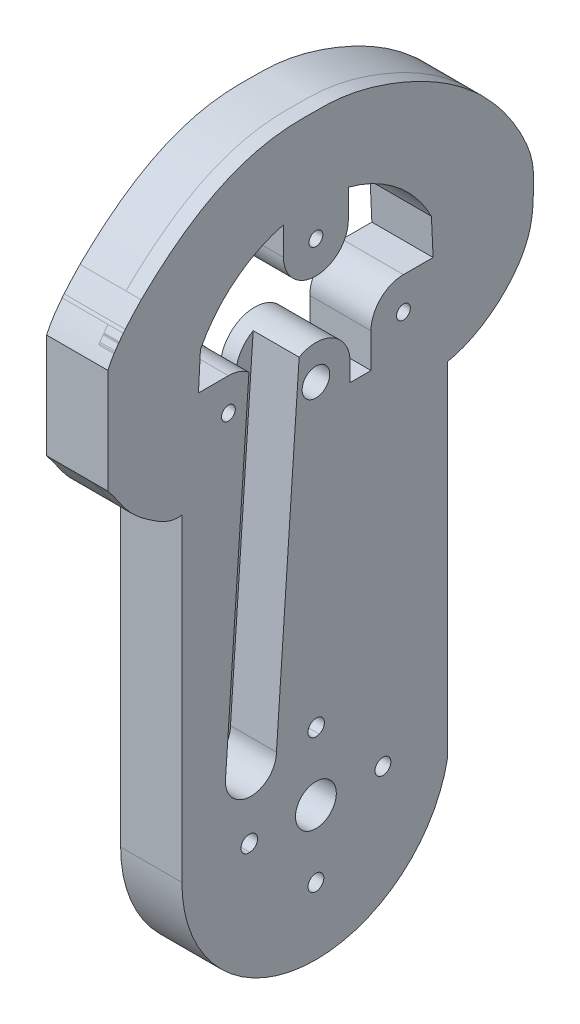
SolidWorks part; units mm, degrees
ref_plane "Plan de face" through (0, 0, 0) normal (0, 0, 1) x (1, 0, 0)
ref_plane "Plan de dessus" through (0, 0, 0) normal (0, 1, 0) x (1, 0, 0)
ref_plane "Plan de droite" through (0, 0, 0) normal (1, 0, 0) x (0, 0, -1)
sketch "Esquisse1" plane through (0, 0, 0) normal (1, 0, 0) x (0, 0, -1)
  line L19 (-6.1849, 6.1035) -> (-6.1849, 11.6469)
  line L20 (6.5151, 6.1035) -> (6.5151, 11.6469)
  line L21 (-10.6299, -14.9225) -> (-10.6299, -21.6694)
  line L22 (-16.9799, -8.5725) -> (-22.849, -8.5725)
  line L23 (17.3101, -8.5725) -> (23.1259, -8.5725)
  line L24 (-40.6082, -16.1449) -> (-40.6083, -16.3483)
  line L25 (0.1651, -90) -> (0.1651, -116.2575) construction
  line L26 (10.9601, -14.9225) -> (10.9601, -21.6694)
  line L27 (0.1651, 0) -> (0.1651, -90) construction
  line L28 (-26.0924, -27.6543) -> (-26.0924, -90) construction
  line L29 (10.9601, -21.6694) -> (6.8802, -21.6694)
  line L30 (6.8802, -21.6694) -> (6.8802, -18.2245)
  line L31 (-6.55, -18.2245) -> (-6.55, -21.6694)
  line L32 (-6.55, -21.6694) -> (-10.6299, -21.6694)
  line L33 (-26.0924, -90) -> (25.954, -90) construction
  line L34 (25.954, -90) -> (25.954, -27.6542) construction
  line L35 (-40.6082, 4.1425) -> (-40.6082, -12.7)
  line L36 (-26.0924, -27.6543) -> (-26.0924, -90)
  line L37 (25.954, -27.6542) -> (25.954, -90)
  line L38 (-40.6082, -16.1449) -> (-40.6082, -12.7)
  line L39 (-37.9035, 8.4934) -> (-36.4387, 10.3053) construction
  line L40 (-22.4631, -1.4086) -> (-22.849, -8.5725)
  line L41 (22.7933, -1.4086) -> (23.1259, -8.5725)
  circle A4 centre (-16.9799, -14.9225) radius 1.3525
  arc A5 (22.7933, -1.4086) -> (6.5151, 11.6469) centre (0.1651, -12.9465) ccw
  arc A6 (6.8802, -18.2245) -> (-6.55, -18.2245) centre (0.1651, -18.2245) ccw
  arc A7 (-37.1666, 9.4049) -> (-37.5578, 8.9143) centre (-0.9364, -19.8843) ccw
  circle A8 centre (0.1651, -18.2245) radius 2.7051
  circle A9 centre (17.3101, -14.9225) radius 1.3525
  circle A10 centre (0.1651, 6.1035) radius 1.3525
  arc A11 (-6.1849, 6.1035) -> (6.5151, 6.1035) centre (0.1651, 6.1035) ccw
  arc A12 (-6.1849, 11.6469) -> (-22.4631, -1.4086) centre (0.1651, -12.9465) ccw
  arc A13 (-10.6299, -14.9225) -> (-16.9799, -8.5725) centre (-16.9799, -14.9225) ccw
  arc A14 (-26.0924, -90) -> (25.954, -85.0614) centre (0.1651, -90) ccw
  arc A15 (17.3101, -8.5725) -> (10.9601, -14.9225) centre (17.3101, -14.9225) ccw
  circle A16 centre (0.1651, -103.1288) radius 1.55
  circle A17 centre (-12.9637, -90) radius 1.55
  circle A18 centre (0.1651, -76.8712) radius 1.55
  circle A19 centre (13.2939, -90) radius 1.55
  circle A20 centre (0.1651, -90) radius 4
  spline S5 degree 3 poles (31.4351, 15.2777) (30.2997, 16.3094) (29.1137, 17.2754) (26.6466, 19.0843) (25.3605, 19.9283) (21.4323, 22.2657) (18.7017, 23.5637) (14.4778, 25.2131) (13.0492, 25.7149) (10.8644, 26.3699) (10.1291, 26.5718) (8.6416, 26.9365) (7.8908, 27.0988) (5.638, 27.5124) (4.1274, 27.6937) (2.2253, 27.7687) (1.8441, 27.7755) (1.0809, 27.78) (0.6989, 27.7774) (-0.4463, 27.7791) (-1.2089, 27.7978) (-2.7327, 27.8153) (-3.4921, 27.8063) (-5.0041, 27.74) (-5.757, 27.6849) (-8.0062, 27.4518) (-9.4927, 27.2046) (-11.702, 26.6888) (-12.4349, 26.4915) (-13.8943, 26.0519) (-14.6221, 25.8075) (-16.7654, 25.0122) (-18.1515, 24.4005) (-20.8478, 23.0325) (-22.1587, 22.2775) (-24.7165, 20.6454) (-25.9664, 19.7652) (-28.3913, 17.9197) (-29.5674, 16.9543) (-31.2876, 15.4541) (-31.8538, 14.9457) (-32.9728, 13.9129) (-33.5258, 13.3888) (-34.0661, 12.8498) knots 0 0 0 0 0.0625 0.0625 0.125 0.125 0.25 0.25 0.3125 0.3125 0.34375 0.34375 0.375 0.375 0.4375 0.4375 0.453125 0.453125 0.46875 0.46875 0.5 0.5 0.53125 0.53125 0.5625 0.5625 0.625 0.625 0.65625 0.65625 0.6875 0.6875 0.75 0.75 0.8125 0.8125 0.875 0.875 0.9375 0.9375 0.96875 0.96875 1 1 1 1
  spline S6 degree 3 poles (-40.6083, -16.3483) (-40.3656, -16.6612) (-40.1123, -16.9655) (-39.6302, -17.5937) (-39.4007, -17.9172) (-38.719, -18.8931) (-38.2719, -19.5496) (-37.3385, -20.831) (-36.8555, -21.4585) (-36.0597, -22.3425) (-35.7819, -22.627) (-35.2029, -23.1772) (-34.9007, -23.4435) (-33.9719, -24.2127) (-33.3244, -24.6854) (-32.0108, -25.6045) (-31.3481, -26.0558) (-30.3031, -26.6606) (-29.9483, -26.8487) (-29.2225, -27.185) (-28.8514, -27.3338) (-28.0836, -27.5707) (-27.6853, -27.658) (-27.0907, -27.7154) (-26.8919, -27.7226) (-26.5928, -27.7129) (-26.493, -27.7063) (-26.293, -27.6856) (-26.1927, -27.6705) (-26.0924, -27.6543) knots 0 0 0 0 0.0625 0.0625 0.125 0.125 0.25 0.25 0.375 0.375 0.4375 0.4375 0.5 0.5 0.625 0.625 0.75 0.75 0.8125 0.8125 0.875 0.875 0.9375 0.9375 0.96875 0.96875 0.984375 0.984375 1 1 1 1
  spline S7 degree 3 poles (25.954, -27.6542) (27.1791, -27.4195) (28.3534, -27.0518) (30.0571, -26.3492) (30.6151, -26.0893) (31.7129, -25.5214) (32.2545, -25.2121) (33.8272, -24.2304) (34.814, -23.5021) (36.672, -21.9072) (37.5433, -21.0408) (38.7519, -19.6235) (39.1347, -19.135) (39.851, -18.1314) (40.1855, -17.6153) (40.8014, -16.5506) (41.0826, -16.002) (41.457, -15.1502) (41.5742, -14.8604) (41.7897, -14.2771) (41.888, -13.9835) (42.3347, -12.5068) (42.5462, -11.2963) (42.7176, -9.4515) (42.7506, -8.8307) (42.7729, -7.9005) (42.7754, -7.5904) (42.7756, -6.9702) (42.7721, -6.6601) (42.7721, -6.35) knots 0 0 0 0 0.125 0.125 0.1875 0.1875 0.25 0.25 0.375 0.375 0.5 0.5 0.5625 0.5625 0.625 0.625 0.6875 0.6875 0.71875 0.71875 0.75 0.75 0.875 0.875 0.9375 0.9375 0.96875 0.96875 1 1 1 1
  spline S8 degree 3 poles (42.7721, -6.35) (42.7721, -5.8749) (42.7838, -5.3981) (42.7897, -4.447) (42.7819, -3.973) (42.6725, -2.5632) (42.4992, -1.6375) (42.1063, -0.2679) (41.9541, 0.1856) (41.6148, 1.0877) (41.4301, 1.5303) (40.8449, 2.8393) (40.4166, 3.6895) (39.0468, 6.1905) (38.0131, 7.7873) (36.2917, 10.0821) (35.6885, 10.8307) (34.4365, 12.2817) (33.7862, 12.9857) (33.1121, 13.6686) knots 0 0 0 0 0.0625 0.0625 0.125 0.125 0.25 0.25 0.3125 0.3125 0.375 0.375 0.5 0.5 0.75 0.75 0.875 0.875 1 1 1 1
  spline S9 degree 3 poles (-37.5578, 8.9143) (-38.1429, 8.1702) (-38.7095, 7.4127) (-39.7419, 5.8248) (-40.2031, 4.9988) (-40.6082, 4.1425) knots 0 0 0 0 0.5 0.5 1 1 1 1
  spline S10 degree 3 poles (-34.0661, 12.8498) (-35.1598, 11.6922) (-36.2511, 10.5374) (-37.1666, 9.4049) knots 0 0 0 0 1 1 1 1
  spline S11 degree 2 poles (33.1121, 13.6686) (32.3322, 14.5391) (31.4351, 15.2777) knots 0 0 0 1 1 1
  point P69 (0.1651, -90)
  dimension "D2" = 4
  dimension "D3" = 8
  dimension "D4" = 3.1
  dimension "D1" = 90
extrude "Boss.-Extru.1" add sketch "Esquisse1" along normal blind 3
sketch "Esquisse3" plane through (3, 0, 0) normal (1, 0, 0) x (0, 0, -1)
  line L0 (-6.1849, 6.1035) -> (-6.1849, 11.6469)
  line L1 (6.5151, 6.1035) -> (6.5151, 11.6469)
  line L3 (-16.9799, -8.5725) -> (-22.849, -8.5725)
  line L4 (17.3101, -8.5725) -> (23.1259, -8.5725)
  line L5 (-40.6082, -16.1449) -> (-40.6083, -16.3483)
  line L6 (0.1651, -90) -> (0.1651, -116.2575) construction
  line L7 (10.9601, -14.9225) -> (10.9601, -21.6694)
  line L8 (0.1651, 0) -> (0.1651, -90) construction
  line L9 (-26.0924, -27.6543) -> (-26.0924, -90) construction
  line L10 (10.9601, -21.6694) -> (6.8802, -21.6694)
  line L11 (6.8802, -21.6694) -> (6.8802, -18.2245)
  line L14 (-26.0924, -90) -> (25.954, -90) construction
  line L15 (25.954, -90) -> (25.954, -27.6542) construction
  line L16 (-40.6082, 4.1425) -> (-40.6082, -12.7)
  line L17 (-26.0924, -27.6543) -> (-26.0924, -90)
  line L18 (25.954, -27.6542) -> (25.954, -94.9386)
  line L19 (-40.6082, -16.1449) -> (-40.6082, -12.7)
  line L20 (-37.9035, 8.4934) -> (-36.4387, 10.3053) construction
  line L21 (-22.4631, -1.4086) -> (-22.849, -8.5725)
  line L22 (22.7933, -1.4086) -> (23.1259, -8.5725)
  line L23 (0.2749, -76.8262) -> (-12.8183, -89.9905) construction
  line L24 (-6.2717, -83.4083) -> (-18.8712, -70.8769) construction
  line L25 (0.1651, -18.2245) -> (-16.9799, -14.9225) construction
  line L26 (-12.5714, -77.1426) -> (-8.4074, -16.5735) construction
  line L27 (-10.4894, -46.8581) -> (-15.4659, -46.5159) construction
  line L28 (-17.5244, -76.4584) -> (-12.9562, -10.0101)
  line L29 (-7.5714, -77.1426) -> (-3.1182, -12.3668)
  circle A0 centre (-16.9799, -14.9225) radius 1.3525
  arc A1 (22.7933, -1.4086) -> (6.5151, 11.6469) centre (0.1651, -12.9465) ccw
  arc A2 (6.8802, -18.2245) -> (-3.1182, -12.3668) centre (0.1651, -18.2245) ccw
  arc A3 (-37.1666, 9.4049) -> (-37.5578, 8.9143) centre (-0.9364, -19.8843) ccw
  circle A4 centre (0.1651, -18.2245) radius 2.7051
  circle A5 centre (17.3101, -14.9225) radius 1.3525
  circle A6 centre (0.1651, 6.1035) radius 1.3525
  arc A7 (-6.1849, 6.1035) -> (6.5151, 6.1035) centre (0.1651, 6.1035) ccw
  arc A8 (-6.1849, 11.6469) -> (-22.4631, -1.4086) centre (0.1651, -12.9465) ccw
  arc A9 (-12.9562, -10.0101) -> (-16.9799, -8.5725) centre (-16.9799, -14.9225) ccw
  arc A10 (-26.0924, -90) -> (25.954, -94.9386) centre (0.1651, -90) ccw
  arc A11 (17.3101, -8.5725) -> (10.9601, -14.9225) centre (17.3101, -14.9225) ccw
  circle A12 centre (0.1651, -103.1288) radius 1.55
  circle A13 centre (-12.8183, -89.9905) radius 1.55
  circle A14 centre (0.2749, -76.8262) radius 1.55
  circle A15 centre (13.2939, -90) radius 1.55
  circle A16 centre (0.1651, -90) radius 4
  circle A17 centre (0.1651, -90) radius 26.2575 construction
  arc A18 (-17.5244, -76.4584) -> (-7.5714, -77.1426) centre (-12.5714, -77.1426) ccw
  spline S0 degree 3 poles (31.4351, 15.2777) (30.2997, 16.3094) (29.1137, 17.2754) (26.6466, 19.0843) (25.3605, 19.9283) (21.4323, 22.2657) (18.7017, 23.5637) (14.4778, 25.2131) (13.0492, 25.7149) (10.8644, 26.3699) (10.1291, 26.5718) (8.6416, 26.9365) (7.8908, 27.0988) (5.638, 27.5124) (4.1274, 27.6937) (2.2253, 27.7687) (1.8441, 27.7755) (1.0809, 27.78) (0.6989, 27.7774) (-0.4463, 27.7791) (-1.2089, 27.7978) (-2.7327, 27.8153) (-3.4921, 27.8063) (-5.0041, 27.74) (-5.757, 27.6849) (-8.0062, 27.4518) (-9.4927, 27.2046) (-11.702, 26.6888) (-12.4349, 26.4915) (-13.8943, 26.0519) (-14.6221, 25.8075) (-16.7654, 25.0122) (-18.1515, 24.4005) (-20.8478, 23.0325) (-22.1587, 22.2775) (-24.7165, 20.6454) (-25.9664, 19.7652) (-28.3913, 17.9197) (-29.5674, 16.9543) (-31.2876, 15.4541) (-31.8538, 14.9457) (-32.9728, 13.9129) (-33.5258, 13.3888) (-34.0661, 12.8498) knots 0 0 0 0 0.0625 0.0625 0.125 0.125 0.25 0.25 0.3125 0.3125 0.34375 0.34375 0.375 0.375 0.4375 0.4375 0.453125 0.453125 0.46875 0.46875 0.5 0.5 0.53125 0.53125 0.5625 0.5625 0.625 0.625 0.65625 0.65625 0.6875 0.6875 0.75 0.75 0.8125 0.8125 0.875 0.875 0.9375 0.9375 0.96875 0.96875 1 1 1 1
  spline S1 degree 3 poles (-40.6083, -16.3483) (-40.3656, -16.6612) (-40.1123, -16.9655) (-39.6302, -17.5937) (-39.4007, -17.9172) (-38.719, -18.8931) (-38.2719, -19.5496) (-37.3385, -20.831) (-36.8555, -21.4585) (-36.0597, -22.3425) (-35.7819, -22.627) (-35.2029, -23.1772) (-34.9007, -23.4435) (-33.9719, -24.2127) (-33.3244, -24.6854) (-32.0108, -25.6045) (-31.3481, -26.0558) (-30.3031, -26.6606) (-29.9483, -26.8487) (-29.2225, -27.185) (-28.8514, -27.3338) (-28.0836, -27.5707) (-27.6853, -27.658) (-27.0907, -27.7154) (-26.8919, -27.7226) (-26.5928, -27.7129) (-26.493, -27.7063) (-26.293, -27.6856) (-26.1927, -27.6705) (-26.0924, -27.6543) knots 0 0 0 0 0.0625 0.0625 0.125 0.125 0.25 0.25 0.375 0.375 0.4375 0.4375 0.5 0.5 0.625 0.625 0.75 0.75 0.8125 0.8125 0.875 0.875 0.9375 0.9375 0.96875 0.96875 0.984375 0.984375 1 1 1 1
  spline S2 degree 3 poles (25.954, -27.6542) (27.1791, -27.4195) (28.3534, -27.0518) (30.0571, -26.3492) (30.6151, -26.0893) (31.7129, -25.5214) (32.2545, -25.2121) (33.8272, -24.2304) (34.814, -23.5021) (36.672, -21.9072) (37.5433, -21.0408) (38.7519, -19.6235) (39.1347, -19.135) (39.851, -18.1314) (40.1855, -17.6153) (40.8014, -16.5506) (41.0826, -16.002) (41.457, -15.1502) (41.5742, -14.8604) (41.7897, -14.2771) (41.888, -13.9835) (42.3347, -12.5068) (42.5462, -11.2963) (42.7176, -9.4515) (42.7506, -8.8307) (42.7729, -7.9005) (42.7754, -7.5904) (42.7756, -6.9702) (42.7721, -6.6601) (42.7721, -6.35) knots 0 0 0 0 0.125 0.125 0.1875 0.1875 0.25 0.25 0.375 0.375 0.5 0.5 0.5625 0.5625 0.625 0.625 0.6875 0.6875 0.71875 0.71875 0.75 0.75 0.875 0.875 0.9375 0.9375 0.96875 0.96875 1 1 1 1
  spline S3 degree 3 poles (42.7721, -6.35) (42.7721, -5.8749) (42.7838, -5.3981) (42.7897, -4.447) (42.7819, -3.973) (42.6725, -2.5632) (42.4992, -1.6375) (42.1063, -0.2679) (41.9541, 0.1856) (41.6148, 1.0877) (41.4301, 1.5303) (40.8449, 2.8393) (40.4166, 3.6895) (39.0468, 6.1905) (38.0131, 7.7873) (36.2917, 10.0821) (35.6885, 10.8307) (34.4365, 12.2817) (33.7862, 12.9857) (33.1121, 13.6686) knots 0 0 0 0 0.0625 0.0625 0.125 0.125 0.25 0.25 0.3125 0.3125 0.375 0.375 0.5 0.5 0.75 0.75 0.875 0.875 1 1 1 1
  spline S4 degree 3 poles (-37.5578, 8.9143) (-38.1429, 8.1702) (-38.7095, 7.4127) (-39.7419, 5.8248) (-40.2031, 4.9988) (-40.6082, 4.1425) knots 0 0 0 0 0.5 0.5 1 1 1 1
  spline S5 degree 3 poles (-34.0661, 12.8498) (-35.1598, 11.6922) (-36.2511, 10.5374) (-37.1666, 9.4049) knots 0 0 0 0 1 1 1 1
  spline S6 degree 2 poles (33.1121, 13.6686) (32.3322, 14.5391) (31.4351, 15.2777) knots 0 0 0 1 1 1
  point P57 (0.1651, -90)
  dimension "D2" = 8
  dimension "D3" = 3.1
  dimension "D4" = 10
  dimension "D1" = 90
extrude "Boss.-Extru.2" add sketch "Esquisse3" along normal blind 6
sketch "Esquisse4" plane through (9, 0, 0) normal (1, 0, 0) x (0, 0, -1)
  line L0 (-6.1849, 6.1035) -> (-6.1849, 11.6469)
  line L1 (6.5151, 6.1035) -> (6.5151, 11.6469)
  line L2 (-10.6299, -14.9225) -> (-10.6299, -21.6694)
  line L3 (-16.9799, -8.5725) -> (-22.849, -8.5725)
  line L4 (17.3101, -8.5725) -> (23.1259, -8.5725)
  line L5 (-40.6082, -16.1449) -> (-40.6083, -16.3483)
  line L6 (0.1651, -90) -> (0.1651, -116.2575) construction
  line L7 (10.9601, -14.9225) -> (10.9601, -21.6694)
  line L8 (0.1651, 0) -> (0.1651, -90) construction
  line L9 (-26.0924, -27.6542) -> (-26.0924, -90) construction
  line L10 (10.9601, -21.6694) -> (6.8802, -21.6694)
  line L11 (6.8802, -21.6694) -> (6.8802, -18.2245)
  line L12 (-6.55, -18.2245) -> (-6.55, -21.6694)
  line L13 (-6.55, -21.6694) -> (-10.6299, -21.6694)
  line L14 (-26.0924, -90) -> (25.954, -90) construction
  line L15 (25.954, -90) -> (25.954, -27.6542) construction
  line L16 (-40.6082, 4.1425) -> (-40.6082, -12.7)
  line L17 (-26.0924, -27.6542) -> (-26.0924, -90)
  line L18 (25.954, -27.6542) -> (25.954, -90)
  line L19 (-40.6082, -16.1449) -> (-40.6082, -12.7)
  line L20 (-37.9035, 8.4934) -> (-36.4387, 10.3053) construction
  line L21 (-22.4631, -1.4086) -> (-22.849, -8.5725)
  line L22 (22.7933, -1.4086) -> (23.1259, -8.5725)
  circle A0 centre (-16.9799, -14.9225) radius 1.3525
  arc A1 (22.7933, -1.4086) -> (6.5151, 11.6469) centre (0.1651, -12.9465) ccw
  arc A2 (6.8802, -18.2245) -> (-6.55, -18.2245) centre (0.1651, -18.2245) ccw
  arc A3 (-37.1666, 9.4049) -> (-37.5578, 8.9143) centre (-0.9364, -19.8843) ccw
  circle A4 centre (0.1651, -18.2245) radius 2.7051
  circle A5 centre (17.3101, -14.9225) radius 1.3525
  circle A6 centre (0.1651, 6.1035) radius 1.3525
  arc A7 (-6.1849, 6.1035) -> (6.5151, 6.1035) centre (0.1651, 6.1035) ccw
  arc A8 (-6.1849, 11.6469) -> (-22.4631, -1.4086) centre (0.1651, -12.9465) ccw
  arc A9 (-10.6299, -14.9225) -> (-16.9799, -8.5725) centre (-16.9799, -14.9225) ccw
  arc A10 (-26.0924, -90) -> (25.954, -85.0614) centre (0.1651, -90) ccw
  arc A11 (17.3101, -8.5725) -> (10.9601, -14.9225) centre (17.3101, -14.9225) ccw
  circle A12 centre (0.1651, -103.1288) radius 1.55
  circle A13 centre (-12.9637, -90) radius 1.55
  circle A14 centre (0.1651, -76.8712) radius 1.55
  circle A15 centre (13.2939, -90) radius 1.55
  circle A16 centre (0.1651, -90) radius 4
  circle A17 centre (-12.5714, -77.1426) radius 5
  spline S0 degree 3 poles (31.4351, 15.2777) (30.2997, 16.3094) (29.1137, 17.2754) (26.6466, 19.0843) (25.3605, 19.9283) (21.4323, 22.2657) (18.7017, 23.5637) (14.4778, 25.2131) (13.0492, 25.7149) (10.8644, 26.3699) (10.1291, 26.5718) (8.6416, 26.9365) (7.8908, 27.0988) (5.638, 27.5124) (4.1274, 27.6937) (2.2253, 27.7687) (1.8441, 27.7755) (1.0809, 27.78) (0.6989, 27.7774) (-0.4463, 27.7791) (-1.2089, 27.7978) (-2.7327, 27.8153) (-3.4921, 27.8063) (-5.0041, 27.74) (-5.757, 27.6849) (-8.0062, 27.4518) (-9.4927, 27.2046) (-11.702, 26.6888) (-12.4349, 26.4915) (-13.8943, 26.0519) (-14.6221, 25.8075) (-16.7654, 25.0122) (-18.1515, 24.4005) (-20.8478, 23.0325) (-22.1587, 22.2775) (-24.7165, 20.6454) (-25.9664, 19.7652) (-28.3913, 17.9197) (-29.5674, 16.9543) (-31.2876, 15.4541) (-31.8538, 14.9457) (-32.9728, 13.9129) (-33.5258, 13.3888) (-34.0661, 12.8498) knots 0 0 0 0 0.0625 0.0625 0.125 0.125 0.25 0.25 0.3125 0.3125 0.34375 0.34375 0.375 0.375 0.4375 0.4375 0.453125 0.453125 0.46875 0.46875 0.5 0.5 0.53125 0.53125 0.5625 0.5625 0.625 0.625 0.65625 0.65625 0.6875 0.6875 0.75 0.75 0.8125 0.8125 0.875 0.875 0.9375 0.9375 0.96875 0.96875 1 1 1 1
  spline S1 degree 3 poles (-40.6083, -16.3483) (-40.3656, -16.6612) (-40.1123, -16.9655) (-39.6302, -17.5937) (-39.4007, -17.9172) (-38.719, -18.8931) (-38.2719, -19.5496) (-37.3385, -20.831) (-36.8555, -21.4585) (-36.0597, -22.3425) (-35.7819, -22.627) (-35.2029, -23.1772) (-34.9007, -23.4435) (-33.9719, -24.2127) (-33.3244, -24.6854) (-32.0108, -25.6045) (-31.3481, -26.0558) (-30.3031, -26.6606) (-29.9483, -26.8487) (-29.2225, -27.185) (-28.8514, -27.3338) (-28.0836, -27.5707) (-27.6853, -27.658) (-27.0907, -27.7154) (-26.8919, -27.7226) (-26.5928, -27.7129) (-26.493, -27.7063) (-26.293, -27.6856) (-26.1927, -27.6705) (-26.0924, -27.6542) knots 0 0 0 0 0.0625 0.0625 0.125 0.125 0.25 0.25 0.375 0.375 0.4375 0.4375 0.5 0.5 0.625 0.625 0.75 0.75 0.8125 0.8125 0.875 0.875 0.9375 0.9375 0.96875 0.96875 0.984375 0.984375 1 1 1 1
  spline S2 degree 3 poles (25.954, -27.6542) (27.1791, -27.4195) (28.3534, -27.0518) (30.0571, -26.3492) (30.6151, -26.0893) (31.7129, -25.5214) (32.2545, -25.2121) (33.8272, -24.2304) (34.814, -23.5021) (36.672, -21.9072) (37.5433, -21.0408) (38.7519, -19.6235) (39.1347, -19.135) (39.851, -18.1314) (40.1855, -17.6153) (40.8014, -16.5506) (41.0826, -16.002) (41.457, -15.1502) (41.5742, -14.8604) (41.7897, -14.2771) (41.888, -13.9835) (42.3347, -12.5068) (42.5462, -11.2963) (42.7176, -9.4515) (42.7506, -8.8307) (42.7729, -7.9005) (42.7754, -7.5904) (42.7756, -6.9702) (42.7721, -6.6601) (42.7721, -6.35) knots 0 0 0 0 0.125 0.125 0.1875 0.1875 0.25 0.25 0.375 0.375 0.5 0.5 0.5625 0.5625 0.625 0.625 0.6875 0.6875 0.71875 0.71875 0.75 0.75 0.875 0.875 0.9375 0.9375 0.96875 0.96875 1 1 1 1
  spline S3 degree 3 poles (42.7721, -6.35) (42.7721, -5.8749) (42.7838, -5.3981) (42.7897, -4.447) (42.7819, -3.973) (42.6725, -2.5632) (42.4992, -1.6375) (42.1063, -0.2679) (41.9541, 0.1856) (41.6148, 1.0877) (41.4301, 1.5303) (40.8449, 2.8393) (40.4166, 3.6895) (39.0468, 6.1905) (38.0131, 7.7873) (36.2917, 10.0821) (35.6885, 10.8307) (34.4365, 12.2817) (33.7862, 12.9857) (33.1121, 13.6686) knots 0 0 0 0 0.0625 0.0625 0.125 0.125 0.25 0.25 0.3125 0.3125 0.375 0.375 0.5 0.5 0.75 0.75 0.875 0.875 1 1 1 1
  spline S4 degree 3 poles (-37.5578, 8.9143) (-38.1429, 8.1702) (-38.7095, 7.4127) (-39.7419, 5.8248) (-40.2031, 4.9988) (-40.6082, 4.1425) knots 0 0 0 0 0.5 0.5 1 1 1 1
  spline S5 degree 3 poles (-34.0661, 12.8498) (-35.1598, 11.6922) (-36.2511, 10.5374) (-37.1666, 9.4049) knots 0 0 0 0 1 1 1 1
  spline S6 degree 2 poles (33.1121, 13.6686) (32.3322, 14.5391) (31.4351, 15.2777) knots 0 0 0 1 1 1
  point P57 (0.1651, -90)
  dimension "D2" = 8
  dimension "D3" = 3.1
  dimension "D1" = 90
extrude "Boss.-Extru.3" add sketch "Esquisse4" along normal blind 3
